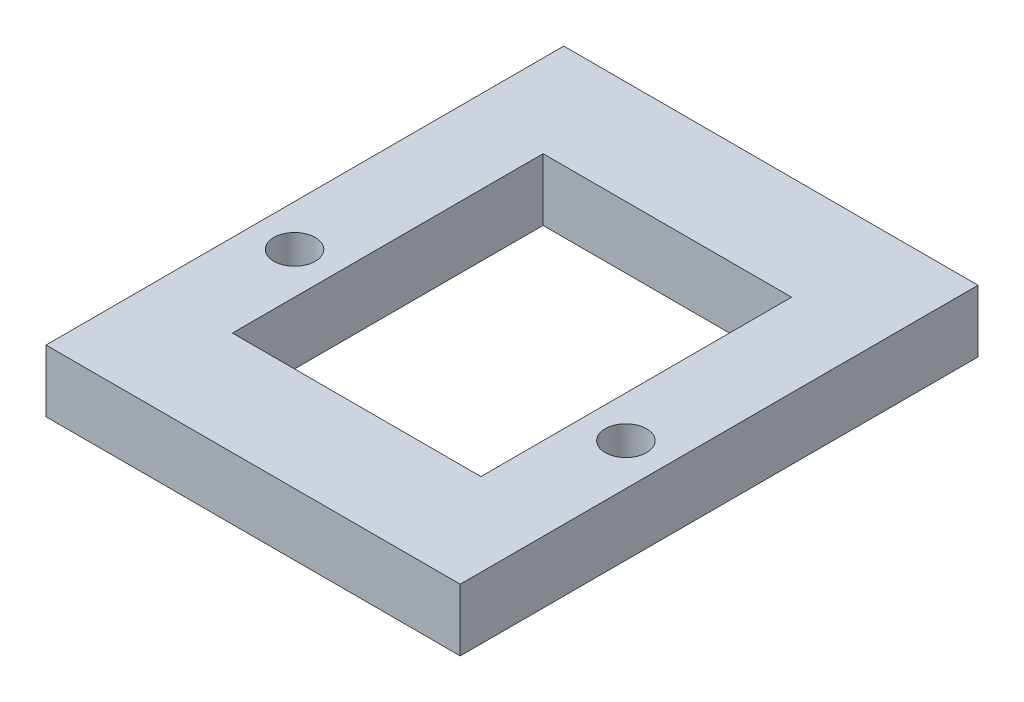
SolidWorks part; units mm, degrees
ref_plane "Front Plane" through (0, 0, 0) normal (0, 0, 1) x (1, 0, 0)
ref_plane "Top Plane" through (0, 0, 0) normal (0, 1, 0) x (1, 0, 0)
ref_plane "Right Plane" through (0, 0, 0) normal (1, 0, 0) x (0, 0, -1)
sketch "Sketch1" plane through (0, 0, 0) normal (0, 1, 0) x (1, 0, 0)
  line L0 (0, 3.5626) -> (0, -3.3501) construction
  line L1 (-10, 12.5) -> (10, 12.5)
  line L2 (-10, 12.5) -> (-10, -12.5)
  line L3 (-10, -12.5) -> (10, -12.5)
  line L4 (10, 12.5) -> (10, -12.5)
  line L5 (-10, 12.5) -> (10, -12.5) construction
  line L6 (-10, -12.5) -> (10, 12.5) construction
  line L7 (-6, 7.5) -> (6, 7.5)
  line L8 (-6, 7.5) -> (-6, -7.5)
  line L9 (-6, -7.5) -> (6, -7.5)
  line L10 (6, 7.5) -> (6, -7.5)
  line L11 (-6, 7.5) -> (6, -7.5) construction
  line L12 (-6, -7.5) -> (6, 7.5) construction
  circle A0 centre (-8, -2.5) radius 1
  circle A1 centre (8, -2.5) radius 1
  point P0 (0, 0)
  point P6 (0, 0)
  dimension "D5" = 2
  dimension "D1" = 20
  dimension "D2" = 25
  dimension "D3" = 5
  dimension "D4" = 4
  dimension "D6" = 10
  dimension "D7" = 2
extrude "Boss-Extrude1" add sketch "Sketch1" along normal mid plane 3
